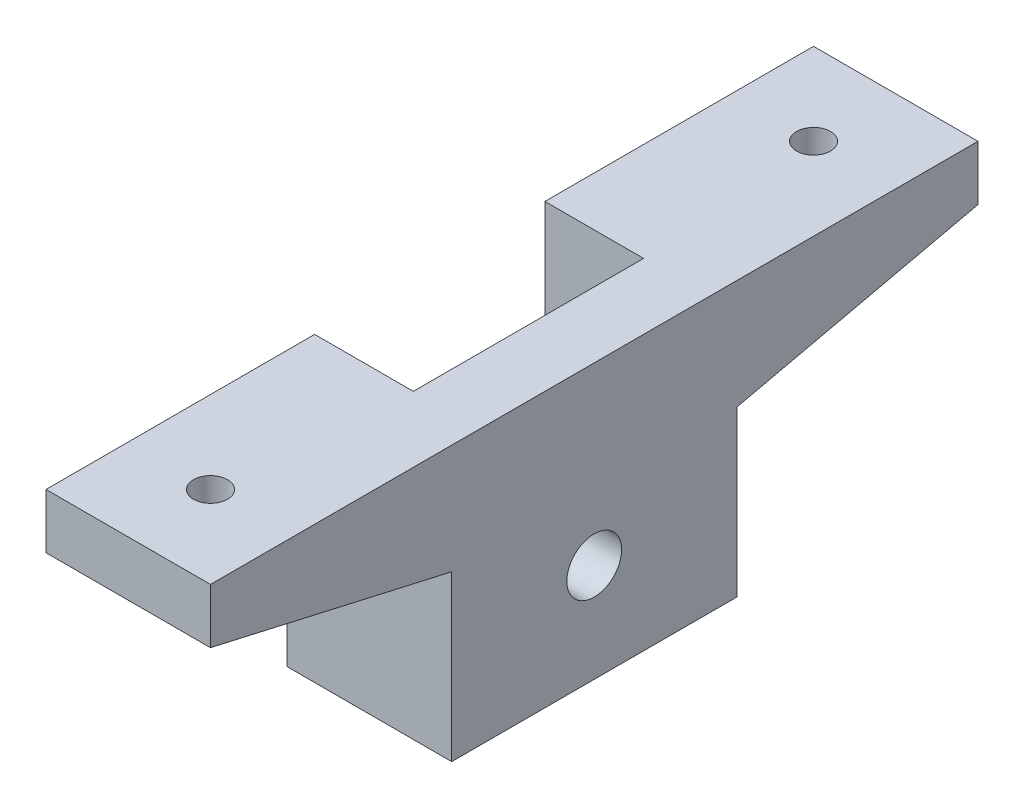
SolidWorks part; units mm, degrees
ref_plane "前视基准面" through (0, 0, 0) normal (0, 0, 1) x (1, 0, 0)
ref_plane "上视基准面" through (0, 0, 0) normal (0, 1, 0) x (1, 0, 0)
ref_plane "右视基准面" through (0, 0, 0) normal (1, 0, 0) x (0, 0, -1)
sketch "草图1" plane through (0, 0, 0) normal (0, 1, 0) x (1, 0, 0)
  line L0 (0, 0) -> (15, 0)
  line L1 (15, 0) -> (15, -70)
  line L2 (15, -70) -> (0, -70)
  line L3 (0, -70) -> (0, 0)
  dimension "D1" = 15
  dimension "D2" = 70
extrude "凸台-拉伸1" add sketch "草图1" along normal blind 25
sketch "草图2" plane through (15, 0, 0) normal (1, 0, 0) x (0, 0, -1)
  line L0 (-70, 20) -> (-48, 15)
  line L1 (-70, 25) -> (-70, 0) construction
  line L2 (-48, 15) -> (-48, 0)
  line L3 (-70, 0) -> (0, 0) construction
  line L4 (-48, 0) -> (-70, 0)
  line L5 (-70, 0) -> (-70, 20)
  line L6 (0, 20) -> (-22, 15)
  line L7 (0, 25) -> (0, 0) construction
  line L8 (-22, 15) -> (-22, 0)
  line L9 (-22, 0) -> (0, 0)
  line L10 (0, 0) -> (0, 20)
  line L11 (-35, 25) -> (-35, 0) construction
  line L12 (-70, 25) -> (0, 25) construction
  point P20 (-40, 30)
  point P22 (-40, 20.0475)
  point P23 (-33, 14.0019)
  dimension "D1" = 5
  dimension "D2" = 10
  dimension "D3" = 26
extrude "切除-拉伸1" cut sketch "草图2" against normal blind 40
sketch "草图3" plane through (0, 25, 0) normal (0, 1, 0) x (1, 0, 0)
  line L0 (0, -24.5) -> (9, -24.5)
  line L1 (0, 0) -> (0, -70) construction
  line L2 (9, -24.5) -> (9, -45.5)
  line L3 (9, -45.5) -> (0, -45.5)
  line L4 (0, -45.5) -> (0, -24.5)
  line L5 (9, -35) -> (15, -35) construction
  line L6 (15, -70) -> (15, 0) construction
  dimension "D1" = 21
  dimension "D2" = 9
extrude "切除-拉伸2" cut sketch "草图3" against normal through all
sketch "草图5" plane through (0, 25, 0) normal (0, 1, 0) x (1, 0, 0)
  line L0 (7.5, -7.5) -> (7.5, -62.5) construction
  line L1 (15, -35) -> (7.5, -35) construction
  line L2 (15, -70) -> (15, 0) construction
  line L4 (15, 0) -> (0, 0) construction
  circle A0 centre (7.5, -7.5) radius 1.55
  circle A1 centre (7.5, -62.5) radius 1.55
  point P8 (0, 0)
  point P10 (10.7999, -3.5487)
  point P12 (7.5, 0)
  point P13 (10.6399, 0)
  dimension "D2" = 3.1
  dimension "D1" = 55
extrude "切除-拉伸3" cut sketch "草图5" against normal through all
sketch "草图6" plane through (15, 0, 0) normal (1, 0, 0) x (0, 0, -1)
  line L0 (-35, 25) -> (-35, 9) construction
  line L1 (-70, 25) -> (0, 25) construction
  line L2 (-48, 0) -> (-22, 0) construction
  circle A0 centre (-35, 9) radius 2.5
  dimension "D1" = 5
  dimension "D2" = 9
extrude "切除-拉伸4" cut sketch "草图6" against normal through all
